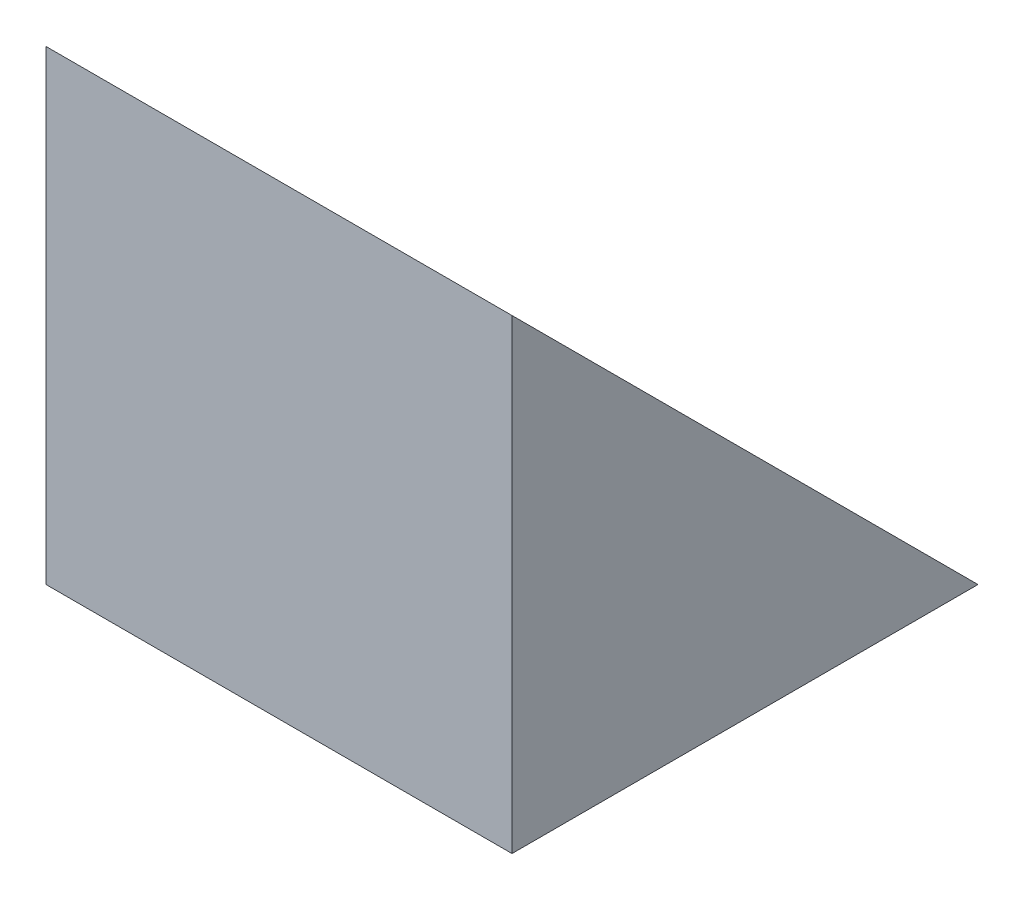
SolidWorks part; units mm, degrees
ref_plane "Přední rovina" through (0, 0, 0) normal (0, 0, 1) x (1, 0, 0)
ref_plane "Horní rovina" through (0, 0, 0) normal (0, 1, 0) x (1, 0, 0)
ref_plane "Pravá rovina" through (0, 0, 0) normal (1, 0, 0) x (0, 0, -1)
sketch "Sketch1" plane through (0, 0, 0) normal (1, 0, 0) x (0, 0, -1)
  line L0 (0, 0) -> (-40, 0)
  line L1 (-40, 0) -> (-40, 40)
  line L2 (-40, 40) -> (0, 0)
  dimension "D1" = 40
  dimension "D2" = 40
extrude "Boss-Extrude1" add sketch "Sketch1" along normal blind 40
